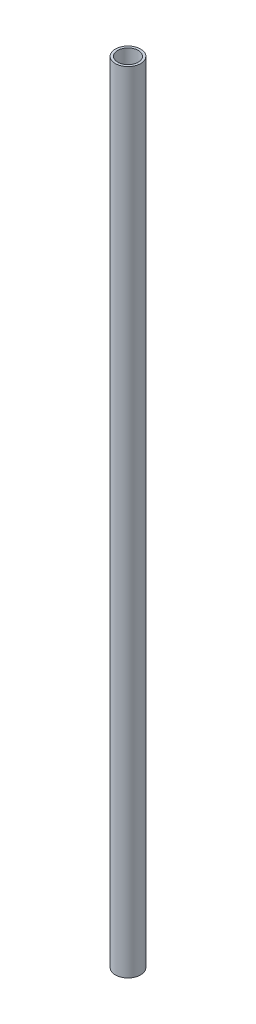
SolidWorks part; units mm, degrees
ref_plane "Front Plane" through (0, 0, 0) normal (0, 0, 1) x (1, 0, 0)
ref_plane "Top Plane" through (0, 0, 0) normal (0, 1, 0) x (1, 0, 0)
ref_plane "Right Plane" through (0, 0, 0) normal (1, 0, 0) x (0, 0, -1)
sketch "Sketch1" plane through (0, 0, 0) normal (0, 1, 0) x (1, 0, 0)
  circle A0 centre (0, 0) radius 6.5
  circle A1 centre (0, 0) radius 8
  dimension "D1" = 13
  dimension "D2" = 16
extrude "Boss-Extrude1" add sketch "Sketch1" along normal blind 500
